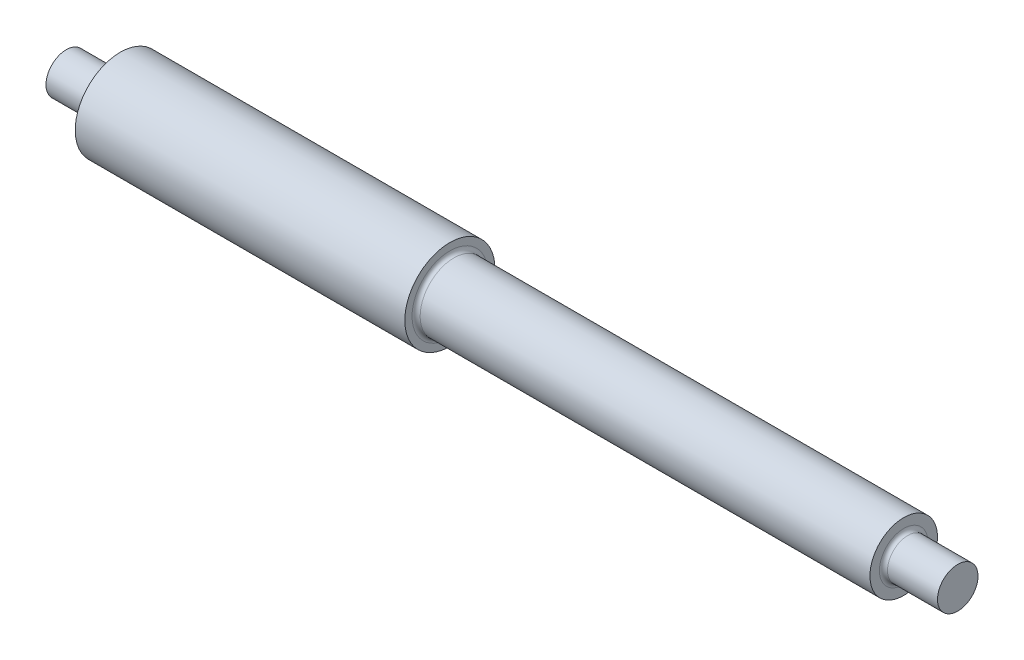
SolidWorks part; units mm, degrees
ref_plane "Front Plane" through (0, 0, 0) normal (0, 0, 1) x (1, 0, 0)
ref_plane "Top Plane" through (0, 0, 0) normal (0, 1, 0) x (1, 0, 0)
ref_plane "Right Plane" through (0, 0, 0) normal (1, 0, 0) x (0, 0, -1)
sketch "Sketch1" plane through (0, 0, 0) normal (0, 0, 1) x (1, 0, 0)
  line L7 (0, 0) -> (0, 7.5)
  line L13 (0, 7.5) -> (18.5, 7.5)
  line L14 (20, 9) -> (20, 16.675)
  line L15 (20, 16.675) -> (142, 16.675)
  line L16 (142, 16.675) -> (142, 14)
  line L17 (143.5, 12.5) -> (310, 12.5)
  line L18 (310, 12.5) -> (310, 9)
  line L19 (311.5, 7.5) -> (330, 7.5)
  line L20 (330, 7.5) -> (330, 0)
  line L21 (330, 0) -> (0, 0)
  arc A0 (311.5, 7.5) -> (310, 9) centre (311.5, 9) cw
  arc A1 (143.5, 12.5) -> (142, 14) centre (143.5, 14) cw
  arc A2 (20, 9) -> (18.5, 7.5) centre (18.5, 9) cw
  point P13 (310, 7.5)
  point P19 (20, 7.5)
  dimension "D9" = 1.5
  dimension "D1" = 330
  dimension "D2" = 7.5
  dimension "D3" = 20
  dimension "D4" = 16.675
  dimension "D5" = 20
  dimension "D6" = 122
  dimension "D7" = 12.5
  dimension "D8" = 7.5
revolve "Revolve1" add sketch "Sketch1" angle 360 about L21
